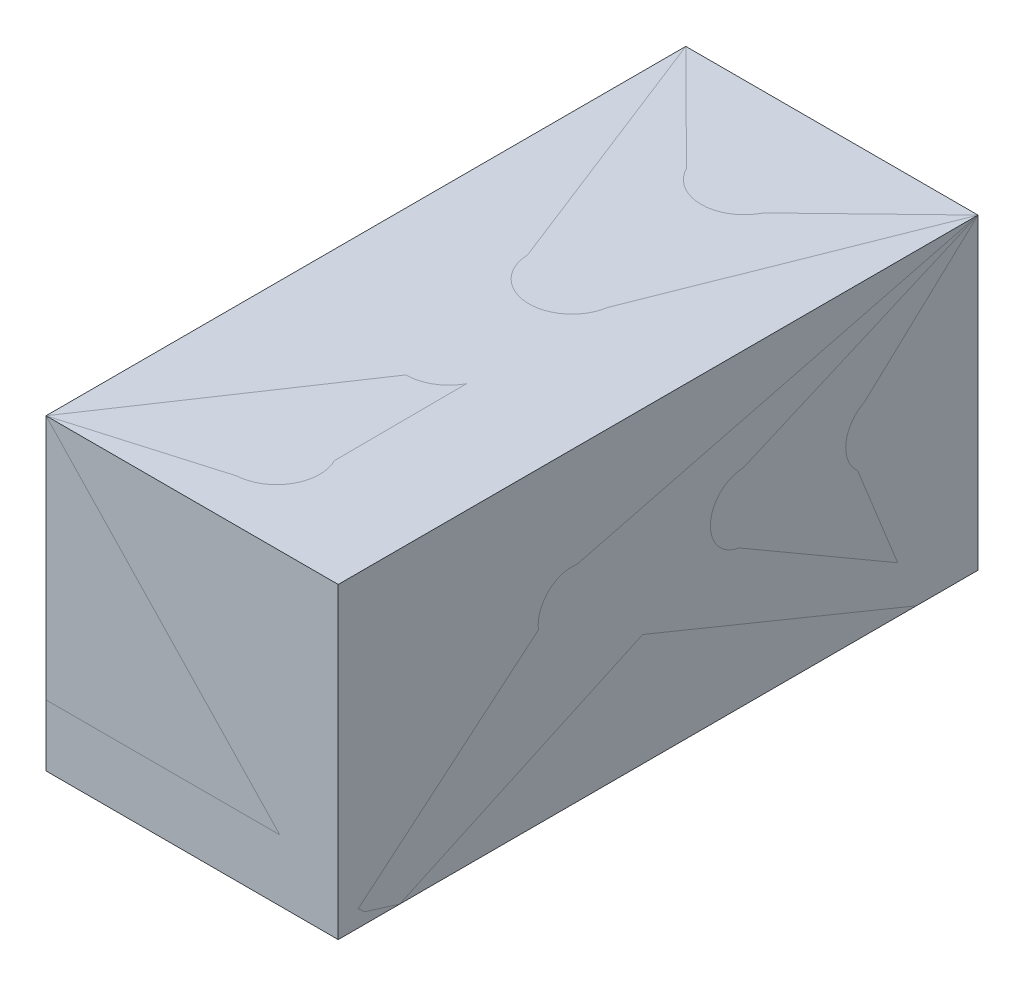
SolidWorks part; units mm, degrees
other "Symétrie_D"
ref_plane "Plan de face" through (0, 0, 0) normal (0, 0, 1) x (1, 0, 0)
ref_plane "Plan de dessus" through (0, 0, 0) normal (0, 1, 0) x (1, 0, 0)
ref_plane "Plan de droite" through (0, 0, 0) normal (1, 0, 0) x (0, 0, -1)
sketch "Esquisse1" plane through (0, 0, 0) normal (0, 0, 1) x (1, 0, 0)
  line L0 (0, 168.6) -> (3.175, 168.6) construction
  line L1 (0, 168.6) -> (-23.75, 168.6)
  line L2 (0, 168.6) -> (0, 193.6)
  line L3 (0, 193.6) -> (-23.75, 193.6)
  line L4 (-23.75, 168.6) -> (-23.75, 193.6)
  line L5 (-23.75, 95) -> (-23.75, 75) construction
  line L7 (0, 198.6) -> (0, 173.6) construction
  dimension "D1" = 25
extrude "Boss.-Extru.1" add sketch "Esquisse1" against normal blind 52
sketch "Esquisse2" plane through (0, 168.6, 0) normal (0, -1, 0) x (1, 0, 0)
  line L0 (-7.9, -45) -> (-7.9, -31.5188)
  line L1 (-16.1, -31.5188) -> (-16.1, -45)
  line L2 (-4.5, -21) -> (-4.5, -27)
  line L3 (-5.5, -28) -> (-7.2911, -28)
  line L4 (-12.3041, -13.5062) -> (-18.5, -13.5062)
  line L5 (-19.5, -14.5062) -> (-19.5, -21)
  line L8 (-12.3, -28.4303) -> (-12.3, -24.9887)
  line L9 (-11.7, -24.9887) -> (-11.7, -28.4303)
  line L10 (-11.7, -13.6061) -> (-11.7, -17.0113)
  line L11 (-6, -25.3313) -> (-6, -16.6687)
  line L12 (-8, -45) -> (-8, -31.5188)
  line L13 (-16, -31.5188) -> (-16, -45)
  line L14 (-18, -16.6687) -> (-18, -25.3313)
  line L15 (-12.3, -17.0113) -> (-12.3, -13.6061)
  line L20 (-8, -45) -> (-8, -31.5188) construction
  line L21 (-16, -31.5188) -> (-16, -45) construction
  arc A0 (-6, -25.3313) -> (-6, -16.6687) centre (-12, -21) ccw construction
  arc A1 (-6, -25.3313) -> (-6, -16.6687) centre (-12, -21) ccw construction
  arc A2 (-18, -16.6687) -> (-18, -25.3313) centre (-12, -21) ccw construction
  arc A3 (-18, -16.6687) -> (-18, -25.3313) centre (-12, -21) ccw construction
  arc A4 (-11.7, -13.6061) -> (-12.3, -13.6061) centre (-12, -21) ccw construction
  arc A5 (-5.9189, -25.3898) -> (-7.9, -31.5188) centre (2.5714, -31.5188) ccw
  arc A6 (-5.9189, -25.3898) -> (-5.9189, -16.6102) centre (-12, -21) ccw
  arc A7 (-5.9189, -16.6102) -> (-11.6959, -13.5062) centre (-12, -21) ccw
  arc A8 (-11.6959, -13.5062) -> (-12.3041, -13.5062) centre (-12, -21) ccw
  arc A10 (-12.3, -17.0113) -> (-12.3, -24.9887) centre (-12, -21) ccw
  arc A11 (-12.3, -28.4303) -> (-12, -31.4) centre (-12, -29.9) ccw
  arc A12 (-12, -31.4) -> (-11.7, -28.4303) centre (-12, -29.9) ccw
  arc A13 (-11.7, -24.9887) -> (-11.7, -17.0113) centre (-12, -21) ccw
  arc A14 (-6, -16.6687) -> (-11.7, -13.6061) centre (-12, -21) ccw
  arc A15 (-6, -25.3313) -> (-8, -31.5188) centre (2.5714, -31.5188) ccw
  arc A16 (-12, -49) -> (-8, -45) centre (-12, -45) ccw
  arc A17 (-16, -45) -> (-12, -49) centre (-12, -45) ccw
  arc A18 (-16, -31.5188) -> (-18, -25.3313) centre (-26.5714, -31.5188) ccw
  arc A19 (-12.3, -13.6061) -> (-18, -16.6687) centre (-12, -21) ccw
  arc A24 (-6, -16.6687) -> (-11.7, -13.6061) centre (-12, -21) ccw construction
  arc A25 (-6, -25.3313) -> (-8, -31.5188) centre (2.5714, -31.5188) ccw construction
  arc A26 (-12, -49) -> (-8, -45) centre (-12, -45) ccw construction
  arc A27 (-16, -45) -> (-12, -49) centre (-12, -45) ccw construction
  arc A28 (-16, -31.5188) -> (-18, -25.3313) centre (-26.5714, -31.5188) ccw construction
  arc A29 (-12.3, -13.6061) -> (-18, -16.6687) centre (-12, -21) ccw construction
  arc A30 (-19.5, -21) -> (-18.0811, -25.3898) centre (-12, -21) ccw
  arc A31 (-16.1, -31.5188) -> (-18.0811, -25.3898) centre (-26.5714, -31.5188) ccw
  arc A32 (-16.1, -45) -> (-12, -49.1) centre (-12, -45) ccw
  arc A33 (-12, -49.1) -> (-7.9, -45) centre (-12, -45) ccw
  arc A34 (-4.5, -27) -> (-5.5, -28) centre (-5.5, -27) cw
  arc A35 (-18.5, -13.5062) -> (-19.5, -14.5062) centre (-18.5, -14.5062) ccw
  arc A36 (-12.3041, -13.5062) -> (-18.0811, -16.6102) centre (-12, -21) ccw construction
  arc A37 (-18.0811, -16.6102) -> (-18.0811, -25.3898) centre (-12, -21) ccw construction
  point P59 (-4.5, -28)
  dimension "D4" = 1
  dimension "D3" = 7
  dimension "D1" = 0
  dimension "D2" = 0.1
extrude "Enlèv. mat.-Extru.1" cut sketch "Esquisse2" against normal blind 6 contours L4 A35 L5 A30 A31 L1 A32 A33 L0 A5 A6 A7 A8
hole_wizard "Chambrage pour vis à tête ronde bombée M31" positions "Esquisse3" profile "Esquisse5" counterbore size "M3" standard "Ansi Metric" end condition up to next
sketch "Esquisse3" plane through (0, 193.6, 0) normal (0, 1, 0) x (1, 0, 0)
  line L16 (-12.3, 24.9887) -> (-12.3, 28.4303)
  line L17 (-11.7, 28.4303) -> (-11.7, 24.9887)
  line L18 (-11.7, 17.0113) -> (-11.7, 13.6061)
  line L19 (-6, 16.6687) -> (-6, 25.3313)
  line L20 (-8, 31.5188) -> (-8, 45)
  line L21 (-16, 45) -> (-16, 31.5188)
  line L22 (-18, 25.3313) -> (-18, 16.6687)
  line L23 (-12.3, 13.6061) -> (-12.3, 17.0113)
  line L24 (-12.3, 24.9887) -> (-12.3, 28.4303) construction
  line L25 (-11.7, 28.4303) -> (-11.7, 24.9887) construction
  line L26 (-11.7, 17.0113) -> (-11.7, 13.6061) construction
  line L27 (-6, 16.6687) -> (-6, 25.3313) construction
  line L28 (-8, 31.5188) -> (-8, 45) construction
  line L29 (-16, 45) -> (-16, 31.5188) construction
  line L30 (-18, 25.3313) -> (-18, 16.6687) construction
  line L31 (-12.3, 13.6061) -> (-12.3, 17.0113) construction
  arc A20 (-12.3, 24.9887) -> (-12.3, 17.0113) centre (-12, 21) ccw
  arc A21 (-12, 31.4) -> (-12.3, 28.4303) centre (-12, 29.9) ccw
  arc A22 (-11.7, 28.4303) -> (-12, 31.4) centre (-12, 29.9) ccw
  arc A23 (-11.7, 17.0113) -> (-11.7, 24.9887) centre (-12, 21) ccw
  arc A24 (-11.7, 13.6061) -> (-6, 16.6687) centre (-12, 21) ccw
  arc A25 (-8, 31.5188) -> (-6, 25.3313) centre (2.5714, 31.5188) ccw
  arc A26 (-8, 45) -> (-12, 49) centre (-12, 45) ccw
  arc A27 (-12, 49) -> (-16, 45) centre (-12, 45) ccw
  arc A28 (-18, 25.3313) -> (-16, 31.5188) centre (-26.5714, 31.5188) ccw
  arc A29 (-18, 16.6687) -> (-12.3, 13.6061) centre (-12, 21) ccw
  arc A30 (-12.3, 24.9887) -> (-12.3, 17.0113) centre (-12, 21) ccw construction
  arc A31 (-12, 31.4) -> (-12.3, 28.4303) centre (-12, 29.9) ccw construction
  arc A32 (-11.7, 28.4303) -> (-12, 31.4) centre (-12, 29.9) ccw construction
  arc A33 (-11.7, 17.0113) -> (-11.7, 24.9887) centre (-12, 21) ccw construction
  arc A34 (-11.7, 13.6061) -> (-6, 16.6687) centre (-12, 21) ccw construction
  arc A35 (-8, 31.5188) -> (-6, 25.3313) centre (2.5714, 31.5188) ccw construction
  arc A36 (-8, 45) -> (-12, 49) centre (-12, 45) ccw construction
  arc A37 (-12, 49) -> (-16, 45) centre (-12, 45) ccw construction
  arc A38 (-18, 25.3313) -> (-16, 31.5188) centre (-26.5714, 31.5188) ccw construction
  arc A39 (-18, 16.6687) -> (-12.3, 13.6061) centre (-12, 21) ccw construction
  point P0 (-12, 21)
  point P2 (-12, 45)
  dimension "D1" = 0
sketch "Esquisse5" plane through (-12, 193.6, -21) normal (1, 0, 0) x (0, 0, 1)
  line L0 (0, 0) -> (0, 19)
  line L1 (0, 19) -> (1.7, 19)
  line L3 (1.7, 19) -> (1.7, 2.4)
  line L4 (1.7, 2.4) -> (3.5, 2.4)
  line L5 (3.5, 2.4) -> (3.5, 0)
  line L7 (3.5, 0) -> (0, 0)
  line L11 (0, -6.35) -> (0, 107.95) construction
  dimension "Diamètre du perçage jusqu'au prochain" = 3.4
  dimension "Profondeur du perçage jusqu'au prochain" = 19
  dimension "Diamètre du chambrage" = 7
  dimension "Profondeur du chambrage" = 2.4
hole_wizard "Dégagement M51" positions "Esquisse3D1" profile "Esquisse6" hole size "M5" standard "Ansi Metric" end condition through all
sketch3d "Esquisse3D1"
  line L1 (0, 168.6, -52) -> (0, 168.6, 0) construction
  line L2 (0, 168.6, 0) -> (0, 193.6, 0) construction
  point P0 (0, 182.6, -8)
  point P2 (0, 182.6, -33)
  dimension "D1" = 14
  dimension "D2" = 25
  dimension "D3" = 8
sketch "Esquisse6" plane through (0, 182.6, -8) normal (0, 1, 0) x (0, 0, -1)
  line L0 (0, 0) -> (0, 23.75)
  line L1 (0, 23.75) -> (2.75, 23.75)
  line L2 (2.75, 23.75) -> (2.75, 0)
  line L5 (2.75, 0) -> (0, 0)
  line L11 (0, -6.35) -> (0, 107.95) construction
  dimension "Diamètre du perçage jusqu'au prochain" = 5.5
  dimension "Profondeur du perçage jusqu'au prochain" = 23.75
ref_plane "Plan1" through (0, 0, -26) normal (0, 0, 1) x (1, 0, 0)
fillet "Congé2" radius 5 1 edges at (-11.875, 168.6, 0)
mirror "Symétrie1" about plane through (0, 0, -26) normal (0, 0, 1) of bodies 104
